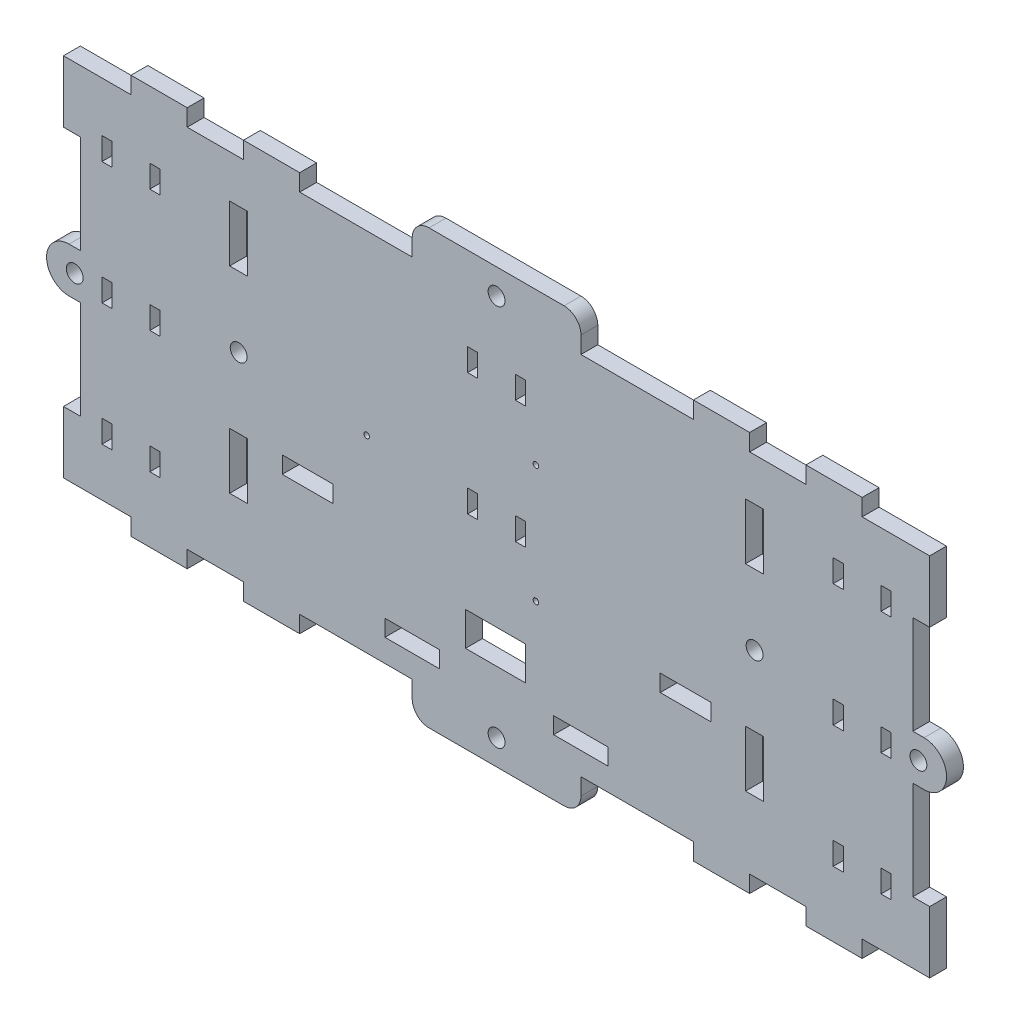
SolidWorks part; units mm, degrees
material "Balsa"
ref_plane "Alzado" through (0, 0, 0) normal (0, 0, 1) x (1, 0, 0)
ref_plane "Planta" through (0, 0, 0) normal (0, 1, 0) x (1, 0, 0)
ref_plane "Vista lateral" through (0, 0, 0) normal (1, 0, 0) x (0, 0, -1)
sketch "Croquis2" plane through (0, 0, 0) normal (0, 0, 1) x (1, 0, 0)
  line L0 (33574.2904, 12864.3834) -> (33573.6603, 12864.3834)
  line L1 (33573.454, 12864.3834) -> (33572.4904, 12864.3834)
  line L2 (33572.4904, 12868.3834) -> (33572.4904, 12866.6236)
  line L3 (33572.4904, 12866.4173) -> (33572.4904, 12864.3834)
  line L4 (33574.2904, 12868.3834) -> (33573.6514, 12868.3834)
  line L5 (33573.4629, 12868.3834) -> (33572.4904, 12868.3834)
  line L6 (33574.2904, 12868.3834) -> (33574.2904, 12866.6236)
  line L7 (33574.2904, 12866.4349) -> (33574.2904, 12864.3834)
  line L8 (33695.7904, 12868.3834) -> (33695.7904, 12866.338)
  line L9 (33695.7904, 12866.038) -> (33695.7904, 12864.3834)
  line L10 (33693.9904, 12864.3834) -> (33694.9231, 12864.3834)
  line L11 (33695.1622, 12864.3834) -> (33695.7904, 12864.3834)
  line L12 (33693.9904, 12868.3834) -> (33693.9904, 12866.338)
  line L13 (33693.9904, 12866.038) -> (33693.9904, 12864.3834)
  line L14 (33693.9904, 12868.3834) -> (33694.8622, 12868.3834)
  line L15 (33695.1622, 12868.3834) -> (33695.7904, 12868.3834)
  line L16 (33708.1404, 12866.7684) -> (33708.1404, 12884.2684)
  line L17 (33708.1409, 12892.2683) -> (33708.1404, 12909.7684)
  line L18 (33708.1404, 12909.7684) -> (33711.1404, 12909.7684)
  line L19 (33711.1404, 12909.7684) -> (33711.1404, 12920.7684)
  line L20 (33702.4904, 12868.3834) -> (33702.4904, 12866.6236)
  line L21 (33699.1404, 12920.7684) -> (33711.1404, 12920.7684)
  line L22 (33702.4904, 12868.3834) -> (33703.4629, 12868.3834)
  line L23 (33689.1404, 12920.7684) -> (33679.1404, 12920.7684)
  line L24 (33695.7904, 12890.1434) -> (33695.7904, 12888.138)
  line L25 (33695.7904, 12887.838) -> (33695.7904, 12886.1434)
  line L26 (33693.9904, 12886.1434) -> (33694.8622, 12886.1434)
  line L27 (33695.1622, 12886.1434) -> (33695.7904, 12886.1434)
  line L28 (33693.9904, 12890.1434) -> (33693.9904, 12888.138)
  line L29 (33693.9904, 12887.838) -> (33693.9904, 12886.1434)
  line L30 (33693.9904, 12890.1434) -> (33694.8622, 12890.1434)
  line L31 (33695.1622, 12890.1434) -> (33695.7904, 12890.1434)
  line L32 (33639.2904, 12890.1434) -> (33639.2904, 12888.5426)
  line L33 (33639.2904, 12888.2426) -> (33639.2904, 12886.1434)
  line L34 (33637.4904, 12886.1434) -> (33638.2998, 12886.1434)
  line L35 (33638.5998, 12886.1434) -> (33639.2904, 12886.1434)
  line L36 (33637.4904, 12890.1434) -> (33637.4904, 12888.5426)
  line L37 (33637.4904, 12888.2426) -> (33637.4904, 12886.1434)
  line L38 (33637.4904, 12890.1434) -> (33638.2998, 12890.1434)
  line L39 (33638.5998, 12890.1434) -> (33639.2904, 12890.1434)
  line L40 (33630.7904, 12890.1434) -> (33630.7904, 12887.8284)
  line L41 (33630.7904, 12887.5284) -> (33630.7904, 12886.1434)
  line L42 (33628.9904, 12886.1434) -> (33629.6397, 12886.1434)
  line L43 (33629.9397, 12886.1434) -> (33630.7904, 12886.1434)
  line L44 (33628.9904, 12890.1434) -> (33628.9904, 12887.8284)
  line L45 (33628.9904, 12887.5284) -> (33628.9904, 12886.1434)
  line L46 (33628.9904, 12890.1434) -> (33629.6397, 12890.1434)
  line L47 (33629.9397, 12890.1434) -> (33630.7904, 12890.1434)
  line L48 (33565.7904, 12864.3834) -> (33565.1013, 12864.3834)
  line L49 (33564.9231, 12864.3834) -> (33563.9904, 12864.3834)
  line L50 (33563.9904, 12868.3834) -> (33563.9904, 12866.338)
  line L51 (33563.9904, 12866.134) -> (33563.9904, 12864.3834)
  line L52 (33565.7904, 12868.3834) -> (33565.1206, 12868.3834)
  line L53 (33564.9038, 12868.3834) -> (33563.9904, 12868.3834)
  line L54 (33565.7904, 12868.3834) -> (33565.7904, 12866.1469)
  line L55 (33565.7904, 12866.038) -> (33565.7904, 12864.3834)
  line L56 (33630.7904, 12911.9034) -> (33630.7904, 12909.4644)
  line L57 (33630.7904, 12909.1644) -> (33630.7904, 12907.9034)
  line L58 (33628.9904, 12907.9034) -> (33629.7448, 12907.9034)
  line L59 (33630.0448, 12907.9034) -> (33630.7904, 12907.9034)
  line L60 (33628.9904, 12911.9034) -> (33628.9904, 12909.4644)
  line L61 (33628.9904, 12909.1644) -> (33628.9904, 12907.9034)
  line L62 (33628.9904, 12911.9034) -> (33629.7448, 12911.9034)
  line L63 (33630.0448, 12911.9034) -> (33630.7904, 12911.9034)
  line L64 (33639.2904, 12911.9034) -> (33639.2904, 12910.1787)
  line L65 (33639.2904, 12909.8787) -> (33639.2904, 12907.9034)
  line L66 (33637.4904, 12907.9034) -> (33638.4049, 12907.9034)
  line L67 (33638.7049, 12907.9034) -> (33639.2904, 12907.9034)
  line L68 (33637.4904, 12911.9034) -> (33637.4904, 12910.1787)
  line L69 (33637.4904, 12909.8787) -> (33637.4904, 12907.9034)
  line L70 (33637.4904, 12911.9034) -> (33638.4049, 12911.9034)
  line L71 (33638.7049, 12911.9034) -> (33639.2904, 12911.9034)
  line L72 (33574.2904, 12907.9034) -> (33573.6643, 12907.9034)
  line L73 (33573.45, 12907.9034) -> (33572.4904, 12907.9034)
  line L74 (33572.4904, 12911.9034) -> (33572.4904, 12910.2236)
  line L75 (33572.4904, 12909.9236) -> (33572.4904, 12907.9034)
  line L76 (33574.2904, 12911.9034) -> (33573.6475, 12911.9034)
  line L77 (33573.4668, 12911.9034) -> (33572.4904, 12911.9034)
  line L78 (33574.2904, 12911.9034) -> (33574.2904, 12910.2236)
  line L79 (33574.2904, 12909.9236) -> (33574.2904, 12907.9034)
  line L80 (33704.2904, 12890.1434) -> (33704.2904, 12888.4236)
  line L81 (33704.2904, 12888.1236) -> (33704.2904, 12886.1434)
  line L82 (33702.4904, 12886.1434) -> (33703.452, 12886.1434)
  line L83 (33703.6623, 12886.1434) -> (33704.2904, 12886.1434)
  line L84 (33702.4904, 12890.1434) -> (33702.4904, 12888.4236)
  line L85 (33702.4904, 12888.1236) -> (33702.4904, 12886.1434)
  line L86 (33702.4904, 12890.1434) -> (33703.4648, 12890.1434)
  line L87 (33703.6495, 12890.1434) -> (33704.2904, 12890.1434)
  line L88 (33589.1404, 12920.7684) -> (33579.1404, 12920.7684)
  line L89 (33579.1404, 12920.7684) -> (33579.1404, 12923.7684)
  line L90 (33579.1404, 12923.7684) -> (33569.1404, 12923.7684)
  line L91 (33569.1404, 12923.7684) -> (33569.1404, 12920.7684)
  line L92 (33569.1404, 12920.7684) -> (33557.1404, 12920.7684)
  line L93 (33711.1404, 12855.7684) -> (33711.1404, 12866.7684)
  line L94 (33708.1404, 12866.7684) -> (33711.1404, 12866.7684)
  line L95 (33649.1404, 12920.7684) -> (33669.1404, 12920.7684)
  line L96 (33599.1404, 12920.7684) -> (33619.1404, 12920.7684)
  line L97 (33557.1404, 12909.7684) -> (33557.1404, 12920.7684)
  line L98 (33557.1404, 12909.7684) -> (33560.1404, 12909.7684)
  line L99 (33560.1398, 12892.2684) -> (33560.1404, 12909.7684)
  line L100 (33560.1404, 12866.7684) -> (33560.1404, 12884.2684)
  line L103 (33699.1404, 12920.7684) -> (33699.1404, 12923.7684)
  line L104 (33699.1404, 12923.7684) -> (33689.1404, 12923.7684)
  line L105 (33689.1404, 12923.7684) -> (33689.1404, 12920.7684)
  line L108 (33589.7874, 12868.1738) -> (33586.7874, 12868.1738)
  line L109 (33586.7874, 12878.1738) -> (33589.7874, 12878.1738)
  line L110 (33628.6167, 12871.2684) -> (33633.7142, 12871.2684)
  line L111 (33633.9853, 12871.2684) -> (33639.2457, 12871.2684)
  line L112 (33639.2457, 12871.2684) -> (33639.2457, 12867.7597)
  line L113 (33639.2457, 12867.5773) -> (33639.2457, 12865.2684)
  line L114 (33639.2457, 12865.2684) -> (33633.9401, 12865.2684)
  line L115 (33633.7594, 12865.2684) -> (33628.6167, 12865.2684)
  line L116 (33628.6167, 12865.2684) -> (33628.6167, 12867.5801)
  line L117 (33628.6167, 12867.757) -> (33628.6167, 12871.2684)
  line L118 (33644.2904, 12862.7384) -> (33648.955, 12862.7384)
  line L119 (33649.255, 12862.7384) -> (33653.9904, 12862.7384)
  line L120 (33653.9904, 12862.7384) -> (33653.9904, 12861.6441)
  line L121 (33653.9904, 12861.3441) -> (33653.9904, 12859.7984)
  line L122 (33653.9904, 12859.7984) -> (33649.255, 12859.7984)
  line L123 (33648.955, 12859.7984) -> (33644.2904, 12859.7984)
  line L124 (33644.2904, 12859.7984) -> (33644.2904, 12861.3441)
  line L125 (33644.2904, 12861.6441) -> (33644.2904, 12862.7384)
  line L126 (33589.7874, 12903.1738) -> (33586.7874, 12903.1738)
  line L127 (33586.7874, 12913.1738) -> (33589.7874, 12913.1738)
  line L128 (33681.4934, 12868.1738) -> (33678.4934, 12868.1738)
  line L129 (33678.4934, 12878.1738) -> (33681.4934, 12878.1738)
  line L130 (33681.4934, 12903.1738) -> (33678.4934, 12903.1738)
  line L131 (33678.4934, 12913.1738) -> (33681.4934, 12913.1738)
  line L132 (33614.2904, 12862.7384) -> (33619.0258, 12862.7384)
  line L133 (33619.3258, 12862.7384) -> (33623.9904, 12862.7384)
  line L134 (33623.9904, 12862.7384) -> (33623.9904, 12861.5787)
  line L135 (33623.9904, 12861.4095) -> (33623.9904, 12859.7984)
  line L136 (33623.9904, 12859.7984) -> (33619.3258, 12859.7984)
  line L137 (33619.1419, 12859.7984) -> (33614.2904, 12859.7984)
  line L138 (33614.2904, 12859.7984) -> (33614.2904, 12861.4082)
  line L139 (33614.2904, 12861.5799) -> (33614.2904, 12862.7384)
  line L140 (33605.0404, 12878.7684) -> (33605.0404, 12877.137)
  line L141 (33605.0404, 12876.837) -> (33605.0404, 12875.7684)
  line L142 (33605.0404, 12875.7684) -> (33600.8093, 12875.7684)
  line L143 (33600.5093, 12875.7684) -> (33596.0404, 12875.7684)
  line L144 (33596.0404, 12875.7684) -> (33596.0404, 12876.837)
  line L145 (33596.0404, 12877.137) -> (33596.0404, 12878.7684)
  line L146 (33596.0404, 12878.7684) -> (33600.5093, 12878.7684)
  line L147 (33600.8093, 12878.7684) -> (33605.0404, 12878.7684)
  line L148 (33663.2404, 12875.7684) -> (33663.2404, 12876.91)
  line L149 (33663.2404, 12877.064) -> (33663.2404, 12878.7684)
  line L150 (33663.2404, 12878.7684) -> (33667.4714, 12878.7684)
  line L151 (33667.6637, 12878.7684) -> (33672.2404, 12878.7684)
  line L152 (33672.2404, 12878.7684) -> (33672.2404, 12877.0682)
  line L153 (33672.2404, 12876.9058) -> (33672.2404, 12875.7684)
  line L154 (33565.7904, 12886.1434) -> (33565.1033, 12886.1434)
  line L155 (33564.9211, 12886.1434) -> (33563.9904, 12886.1434)
  line L156 (33563.9904, 12890.1434) -> (33563.9904, 12888.138)
  line L157 (33563.9904, 12887.838) -> (33563.9904, 12886.1434)
  line L158 (33565.7904, 12890.1434) -> (33565.1186, 12890.1434)
  line L159 (33564.9058, 12890.1434) -> (33563.9904, 12890.1434)
  line L160 (33565.7904, 12890.1434) -> (33565.7904, 12888.138)
  line L161 (33565.7904, 12887.838) -> (33565.7904, 12886.1434)
  line L162 (33704.2904, 12911.9034) -> (33704.2904, 12910.2236)
  line L163 (33704.2904, 12909.9236) -> (33704.2904, 12907.9034)
  line L164 (33702.4904, 12907.9034) -> (33703.45, 12907.9034)
  line L165 (33703.6643, 12907.9034) -> (33704.2904, 12907.9034)
  line L166 (33702.4904, 12911.9034) -> (33702.4904, 12910.2236)
  line L167 (33702.4904, 12909.9236) -> (33702.4904, 12907.9034)
  line L168 (33702.4904, 12911.9034) -> (33703.4668, 12911.9034)
  line L169 (33703.6475, 12911.9034) -> (33704.2904, 12911.9034)
  line L170 (33695.7904, 12911.9034) -> (33695.7904, 12909.938)
  line L171 (33695.7904, 12909.7469) -> (33695.7904, 12907.9034)
  line L172 (33693.9904, 12907.9034) -> (33694.8622, 12907.9034)
  line L173 (33695.1622, 12907.9034) -> (33695.7904, 12907.9034)
  line L174 (33693.9904, 12911.9034) -> (33693.9904, 12909.938)
  line L175 (33693.9904, 12909.638) -> (33693.9904, 12907.9034)
  line L176 (33693.9904, 12911.9034) -> (33694.8622, 12911.9034)
  line L177 (33695.1622, 12911.9034) -> (33695.7904, 12911.9034)
  line L178 (33565.7904, 12907.9034) -> (33565.1052, 12907.9034)
  line L179 (33564.9192, 12907.9034) -> (33563.9904, 12907.9034)
  line L180 (33563.9904, 12911.9034) -> (33563.9904, 12909.938)
  line L181 (33563.9904, 12909.638) -> (33563.9904, 12907.9034)
  line L182 (33565.7904, 12911.9034) -> (33565.1166, 12911.9034)
  line L183 (33564.9078, 12911.9034) -> (33563.9904, 12911.9034)
  line L184 (33565.7904, 12911.9034) -> (33565.7904, 12909.938)
  line L185 (33565.7904, 12909.638) -> (33565.7904, 12907.9034)
  line L186 (33574.2904, 12886.1434) -> (33573.6623, 12886.1434)
  line L187 (33573.452, 12886.1434) -> (33572.4904, 12886.1434)
  line L188 (33572.4904, 12890.1434) -> (33572.4904, 12888.4236)
  line L189 (33572.4904, 12888.2173) -> (33572.4904, 12886.1434)
  line L190 (33574.2904, 12890.1434) -> (33573.6495, 12890.1434)
  line L191 (33573.4648, 12890.1434) -> (33572.4904, 12890.1434)
  line L192 (33574.2904, 12890.1434) -> (33574.2904, 12888.4236)
  line L193 (33574.2904, 12888.2349) -> (33574.2904, 12886.1434)
  line L196 (33672.2404, 12875.7684) -> (33667.7714, 12875.7684)
  line L197 (33667.4714, 12875.7684) -> (33663.2404, 12875.7684)
  line L198 (33589.8374, 12903.1738) -> (33589.7874, 12903.1738)
  line L199 (33586.7874, 12903.1738) -> (33586.7374, 12903.1738)
  line L200 (33589.7874, 12913.1738) -> (33589.8874, 12913.1738)
  line L201 (33586.7874, 12913.1738) -> (33586.6874, 12913.1738)
  line L202 (33586.6874, 12913.1738) -> (33586.6874, 12903.1738)
  line L203 (33586.6874, 12903.1738) -> (33586.7374, 12903.1738)
  line L204 (33589.8874, 12913.1738) -> (33589.8874, 12903.1738)
  line L205 (33589.8874, 12903.1738) -> (33589.8374, 12903.1738)
  line L206 (33586.7874, 12878.1738) -> (33586.6874, 12878.1738)
  line L207 (33586.6874, 12878.1738) -> (33586.6874, 12868.1738)
  line L208 (33586.6874, 12868.1738) -> (33586.7874, 12868.1738)
  line L209 (33589.7874, 12868.1738) -> (33589.8874, 12868.1738)
  line L210 (33589.8874, 12868.1738) -> (33589.8874, 12878.1738)
  line L211 (33589.8874, 12878.1738) -> (33589.7874, 12878.1738)
  line L212 (33681.4934, 12878.1738) -> (33681.5934, 12878.1738)
  line L213 (33678.4934, 12878.1738) -> (33678.3934, 12878.1738)
  line L214 (33678.3934, 12878.1738) -> (33678.3934, 12868.1738)
  line L215 (33678.3934, 12868.1738) -> (33678.4934, 12868.1738)
  line L216 (33681.4934, 12868.1738) -> (33681.5934, 12868.1738)
  line L217 (33681.5934, 12868.1738) -> (33681.5934, 12878.1738)
  line L218 (33681.4934, 12913.1738) -> (33681.5934, 12913.1738)
  line L219 (33681.5934, 12913.1738) -> (33681.5934, 12903.1738)
  line L220 (33681.5934, 12903.1738) -> (33681.4934, 12903.1738)
  line L221 (33678.4934, 12903.1738) -> (33678.3934, 12903.1738)
  line L222 (33678.3934, 12903.1738) -> (33678.3934, 12913.1738)
  line L223 (33678.3934, 12913.1738) -> (33678.4934, 12913.1738)
  line L225 (33708.1404, 12884.2684) -> (33710.1404, 12884.2683)
  line L227 (33557.1404, 12855.7684) -> (33557.1404, 12861.0583)
  line L228 (33557.1404, 12861.3529) -> (33557.1404, 12866.7684)
  line L229 (33557.1404, 12866.7684) -> (33558.8155, 12866.7684)
  line L230 (33559.1155, 12866.7684) -> (33560.1404, 12866.7684)
  line L238 (33558.1398, 12892.2683) -> (33560.1398, 12892.2684)
  line L239 (33560.1404, 12884.2684) -> (33558.1404, 12884.2683)
  line L241 (33649.1404, 12920.7684) -> (33649.1404, 12923.7684)
  line L242 (33622.1404, 12926.7684) -> (33646.1404, 12926.7684)
  line L243 (33619.1404, 12923.7684) -> (33619.1404, 12920.7684)
  line L244 (33679.1404, 12920.7684) -> (33679.1404, 12923.7684)
  line L245 (33679.1404, 12923.7684) -> (33669.1404, 12923.7684)
  line L246 (33669.1404, 12923.7684) -> (33669.1404, 12920.7684)
  line L251 (33599.1404, 12920.7684) -> (33599.1404, 12923.7684)
  line L252 (33599.1404, 12923.7684) -> (33589.1404, 12923.7684)
  line L253 (33589.1404, 12923.7684) -> (33589.1404, 12920.7684)
  line L255 (33589.1404, 12855.7684) -> (33579.1404, 12855.7684)
  line L256 (33579.1404, 12855.7684) -> (33579.1404, 12852.7684)
  line L257 (33579.1404, 12852.7684) -> (33569.1404, 12852.7684)
  line L258 (33569.1404, 12852.7684) -> (33569.1404, 12855.7684)
  line L259 (33569.1404, 12855.7684) -> (33557.1404, 12855.7684)
  line L260 (33699.1404, 12855.7684) -> (33699.1404, 12852.7684)
  line L261 (33699.1404, 12852.7684) -> (33689.1404, 12852.7684)
  line L262 (33689.1404, 12852.7684) -> (33689.1404, 12855.7684)
  line L263 (33689.1404, 12855.7684) -> (33685.3093, 12855.7684)
  line L264 (33685.0093, 12855.7684) -> (33679.1404, 12855.7684)
  line L265 (33699.1404, 12855.7684) -> (33711.1404, 12855.7684)
  line L267 (33649.1404, 12855.7684) -> (33649.1404, 12852.7684)
  line L268 (33622.1404, 12849.7684) -> (33646.1404, 12849.7684)
  line L269 (33619.1404, 12852.7684) -> (33619.1404, 12855.7684)
  line L270 (33679.1404, 12855.7684) -> (33679.1404, 12852.7684)
  line L271 (33679.1404, 12852.7684) -> (33669.1404, 12852.7684)
  line L272 (33669.1404, 12852.7684) -> (33669.1404, 12855.7684)
  line L273 (33669.1404, 12855.7684) -> (33665.3093, 12855.7684)
  line L274 (33665.0093, 12855.7684) -> (33659.1404, 12855.7684)
  line L275 (33649.1404, 12855.7684) -> (33659.1404, 12855.7684)
  line L276 (33609.1404, 12855.7684) -> (33599.1404, 12855.7684)
  line L277 (33599.1404, 12855.7684) -> (33599.1404, 12852.7684)
  line L278 (33599.1404, 12852.7684) -> (33589.1404, 12852.7684)
  line L279 (33589.1404, 12852.7684) -> (33589.1404, 12855.7684)
  line L280 (33609.1404, 12855.7684) -> (33619.1404, 12855.7684)
  line L281 (33710.1409, 12892.2683) -> (33708.1409, 12892.2683)
  line L284 (33558.8155, 12866.7684) -> (33559.1155, 12866.7684)
  line L285 (33557.1404, 12861.0583) -> (33557.1404, 12861.3529)
  line L286 (33665.0093, 12855.7684) -> (33665.3093, 12855.7684)
  line L287 (33685.0093, 12855.7684) -> (33685.3093, 12855.7684)
  line L296 (33563.9904, 12907.9034) -> (33565.7904, 12907.9034)
  line L297 (33565.7904, 12907.9034) -> (33565.7904, 12911.9034)
  line L298 (33565.7904, 12911.9034) -> (33563.9904, 12911.9034)
  line L299 (33563.9904, 12911.9034) -> (33563.9904, 12907.9034)
  line L300 (33572.4904, 12907.9034) -> (33574.2904, 12907.9034)
  line L301 (33574.2904, 12907.9034) -> (33574.2904, 12911.9034)
  line L302 (33574.2904, 12911.9034) -> (33572.4904, 12911.9034)
  line L303 (33572.4904, 12911.9034) -> (33572.4904, 12907.9034)
  line L304 (33563.9904, 12886.1434) -> (33565.7904, 12886.1434)
  line L305 (33565.7904, 12886.1434) -> (33565.7904, 12890.1434)
  line L306 (33565.7904, 12890.1434) -> (33563.9904, 12890.1434)
  line L307 (33563.9904, 12890.1434) -> (33563.9904, 12886.1434)
  line L308 (33572.4904, 12886.1434) -> (33574.2904, 12886.1434)
  line L309 (33574.2904, 12886.1434) -> (33574.2904, 12890.1434)
  line L310 (33574.2904, 12890.1434) -> (33572.4904, 12890.1434)
  line L311 (33572.4904, 12890.1434) -> (33572.4904, 12886.1434)
  line L312 (33563.9904, 12864.3834) -> (33565.7904, 12864.3834)
  line L313 (33565.7904, 12864.3834) -> (33565.7904, 12868.3834)
  line L314 (33565.7904, 12868.3834) -> (33563.9904, 12868.3834)
  line L315 (33563.9904, 12868.3834) -> (33563.9904, 12864.3834)
  line L316 (33572.4904, 12864.3834) -> (33574.2904, 12864.3834)
  line L317 (33574.2904, 12864.3834) -> (33574.2904, 12868.3834)
  line L318 (33574.2904, 12868.3834) -> (33572.4904, 12868.3834)
  line L319 (33572.4904, 12868.3834) -> (33572.4904, 12864.3834)
  line L320 (33596.0404, 12875.7684) -> (33605.0404, 12875.7684)
  line L321 (33605.0404, 12875.7684) -> (33605.0404, 12878.7684)
  line L322 (33605.0404, 12878.7684) -> (33596.0404, 12878.7684)
  line L323 (33596.0404, 12878.7684) -> (33596.0404, 12875.7684)
  line L324 (33614.2904, 12859.7984) -> (33623.9904, 12859.7984)
  line L325 (33623.9904, 12859.7984) -> (33623.9904, 12862.7384)
  line L326 (33623.9904, 12862.7384) -> (33614.2904, 12862.7384)
  line L327 (33614.2904, 12862.7384) -> (33614.2904, 12859.7984)
  line L328 (33628.6167, 12865.2684) -> (33639.2457, 12865.2684)
  line L329 (33639.2457, 12865.2684) -> (33639.2457, 12871.2684)
  line L330 (33639.2457, 12871.2684) -> (33628.6167, 12871.2684)
  line L331 (33628.6167, 12871.2684) -> (33628.6167, 12865.2684)
  line L332 (33628.9904, 12886.1434) -> (33630.7904, 12886.1434)
  line L333 (33630.7904, 12886.1434) -> (33630.7904, 12890.1434)
  line L334 (33630.7904, 12890.1434) -> (33628.9904, 12890.1434)
  line L335 (33628.9904, 12890.1434) -> (33628.9904, 12886.1434)
  line L336 (33637.4904, 12886.1434) -> (33639.2904, 12886.1434)
  line L337 (33639.2904, 12886.1434) -> (33639.2904, 12890.1434)
  line L338 (33639.2904, 12890.1434) -> (33637.4904, 12890.1434)
  line L339 (33637.4904, 12890.1434) -> (33637.4904, 12886.1434)
  line L340 (33637.4904, 12911.9034) -> (33639.2904, 12911.9034)
  line L341 (33639.2904, 12911.9034) -> (33639.2904, 12907.9034)
  line L342 (33639.2904, 12907.9034) -> (33637.4904, 12907.9034)
  line L343 (33637.4904, 12907.9034) -> (33637.4904, 12911.9034)
  line L344 (33628.9904, 12911.9034) -> (33630.7904, 12911.9034)
  line L345 (33630.7904, 12911.9034) -> (33630.7904, 12907.9034)
  line L346 (33630.7904, 12907.9034) -> (33628.9904, 12907.9034)
  line L347 (33628.9904, 12907.9034) -> (33628.9904, 12911.9034)
  line L348 (33644.2904, 12859.7984) -> (33653.9904, 12859.7984)
  line L349 (33653.9904, 12859.7984) -> (33653.9904, 12862.7384)
  line L350 (33653.9904, 12862.7384) -> (33644.2904, 12862.7384)
  line L351 (33644.2904, 12862.7384) -> (33644.2904, 12859.7984)
  line L352 (33663.2404, 12875.7684) -> (33672.2404, 12875.7684)
  line L353 (33672.2404, 12875.7684) -> (33672.2404, 12878.7684)
  line L354 (33672.2404, 12878.7684) -> (33663.2404, 12878.7684)
  line L355 (33663.2404, 12878.7684) -> (33663.2404, 12875.7684)
  line L356 (33693.9904, 12911.9034) -> (33695.7904, 12911.9034)
  line L357 (33695.7904, 12911.9034) -> (33695.7904, 12907.9034)
  line L358 (33695.7904, 12907.9034) -> (33693.9904, 12907.9034)
  line L359 (33693.9904, 12907.9034) -> (33693.9904, 12911.9034)
  line L360 (33702.4904, 12907.9034) -> (33704.2904, 12907.9034)
  line L361 (33704.2904, 12907.9034) -> (33704.2904, 12911.9034)
  line L362 (33704.2904, 12911.9034) -> (33702.4904, 12911.9034)
  line L363 (33702.4904, 12911.9034) -> (33702.4904, 12907.9034)
  line L364 (33693.9904, 12890.1434) -> (33695.7904, 12890.1434)
  line L365 (33695.7904, 12890.1434) -> (33695.7904, 12886.1434)
  line L366 (33695.7904, 12886.1434) -> (33693.9904, 12886.1434)
  line L367 (33693.9904, 12886.1434) -> (33693.9904, 12890.1434)
  line L368 (33702.4904, 12890.1434) -> (33704.2904, 12890.1434)
  line L369 (33704.2904, 12890.1434) -> (33704.2904, 12886.1434)
  line L370 (33704.2904, 12886.1434) -> (33702.4904, 12886.1434)
  line L371 (33702.4904, 12886.1434) -> (33702.4904, 12890.1434)
  line L372 (33693.9904, 12864.3834) -> (33695.7904, 12864.3834)
  line L373 (33695.7904, 12864.3834) -> (33695.7904, 12868.3834)
  line L374 (33695.7904, 12868.3834) -> (33693.9904, 12868.3834)
  line L375 (33693.9904, 12868.3834) -> (33693.9904, 12864.3834)
  line L376 (33702.4904, 12864.3834) -> (33704.2904, 12864.3834)
  line L377 (33704.2904, 12864.3834) -> (33704.2904, 12868.3834)
  line L378 (33704.2904, 12868.3834) -> (33702.4904, 12868.3834)
  line L379 (33702.4904, 12868.3834) -> (33702.4904, 12864.3834)
  circle A0 centre (33641.1404, 12899.7684) radius 0.5
  circle A1 centre (33641.1404, 12878.7684) radius 0.5
  circle A2 centre (33680.0118, 12890.6738) radius 1.5
  circle A3 centre (33588.2874, 12890.6738) radius 1.5
  circle A4 centre (33611.0404, 12889.2684) radius 0.5
  circle A5 centre (33709.1406, 12888.2684) radius 1.5
  arc A6 (33710.1404, 12884.2683) -> (33710.1409, 12892.2683) centre (33710.1406, 12888.2683) ccw
  circle A7 centre (33559.1401, 12888.2684) radius 1.5
  arc A8 (33558.1398, 12892.2683) -> (33558.1404, 12884.2683) centre (33558.1401, 12888.2683) ccw
  circle A9 centre (33634.1404, 12922.2684) radius 1.5
  arc A10 (33649.1404, 12923.7684) -> (33646.1404, 12926.7684) centre (33646.1404, 12923.7684) ccw
  arc A11 (33622.1404, 12926.7684) -> (33619.1404, 12923.7684) centre (33622.1404, 12923.7684) ccw
  circle A12 centre (33634.1404, 12854.2684) radius 1.5
  arc A13 (33646.1404, 12849.7684) -> (33649.1404, 12852.7684) centre (33646.1404, 12852.7684) ccw
  arc A14 (33619.1404, 12852.7684) -> (33622.1404, 12849.7684) centre (33622.1404, 12852.7684) ccw
extrude "Saliente-Extruir1" add sketch "Croquis2" along normal blind 3 contours L269 A14 L268 A13 L267 L275 L274 L286 L273 L272 L271 L270 L264 L287 L263 L262 L261 L260 L265 L93 L94 L16 L225 A6 L281 L17 L18 L19 L21 L103 L104 L105 L23 L244 L245 L246 L95 L241 A10 L242 A11 L243 L96 L251 L252 L253 L88 L89 L90 L91 L92
